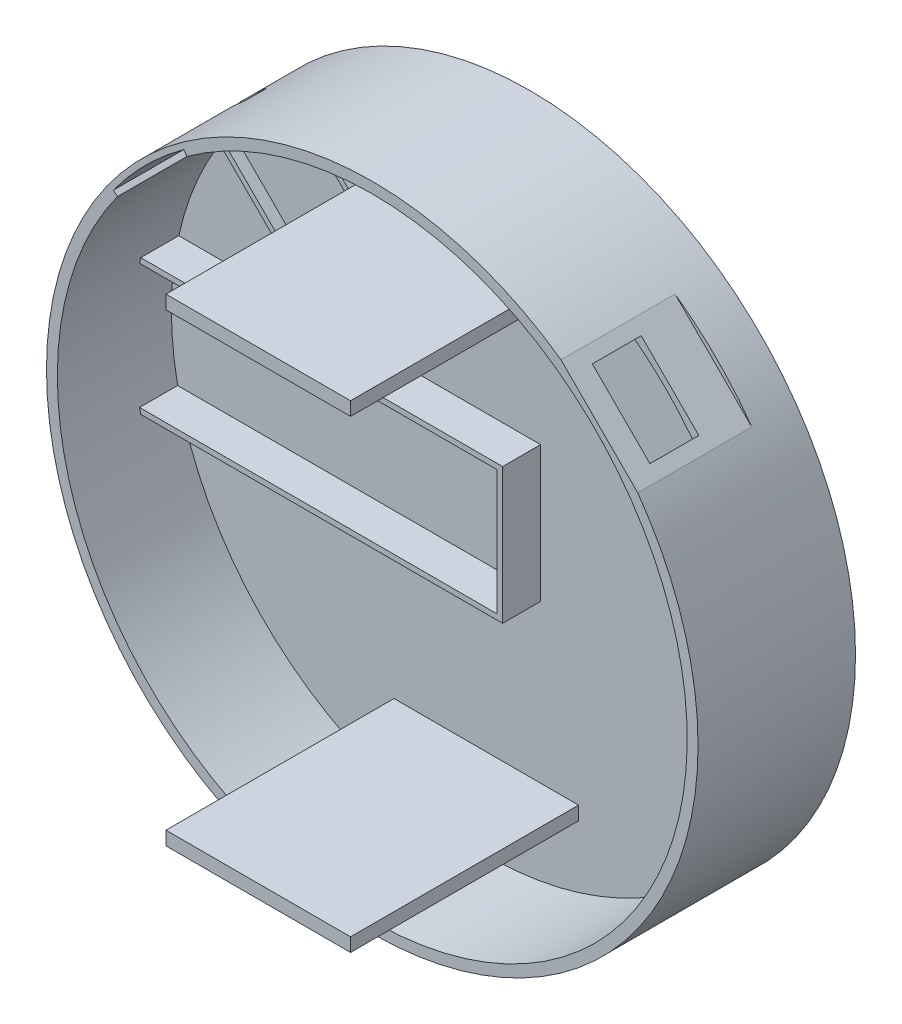
SolidWorks part; units mm, degrees
ref_plane "Alzado" through (0, 0, 0) normal (0, 0, 1) x (1, 0, 0)
ref_plane "Planta" through (0, 0, 0) normal (0, 1, 0) x (1, 0, 0)
ref_plane "Vista lateral" through (0, 0, 0) normal (1, 0, 0) x (0, 0, -1)
sketch "Croquis1" plane through (0, 0, 0) normal (0, 0, 1) x (1, 0, 0)
  circle A0 centre (0, 0) radius 60
  dimension "D1" = 120
extrude "Saliente-Extruir1" add sketch "Croquis1" along normal blind 8
sketch "Croquis2" plane through (0, 0, 8) normal (0, 0, 1) x (1, 0, 0)
  line L0 (-56, 0) -> (-45, 0) construction
  line L1 (-56, 11.5) -> (9, 11.5)
  line L2 (-56, 11.5) -> (-56, -11.5) construction
  line L3 (-56, -11.5) -> (9, -11.5)
  line L4 (9, 11.5) -> (9, -11.5)
  line L5 (-57, 12.5) -> (-57, 11.5)
  line L6 (-57, -12.5) -> (10, -12.5)
  line L7 (10, 12.5) -> (10, -12.5)
  line L8 (-57, 12.5) -> (10, 12.5)
  line L9 (-56, -11.5) -> (-57, -11.5)
  line L10 (-56, 11.5) -> (-57, 11.5)
  line L11 (-57, -11.5) -> (-57, -12.5)
  line L13 (-57, 12.5) -> (-57, -12.5) construction
  point P4 (-56, 0)
  dimension "D1" = 23
  dimension "D2" = 65
  dimension "D3" = 11
  dimension "D4" = 45
  dimension "D5" = 1
extrude "Saliente-Extruir2" add sketch "Croquis2" along normal blind 7
sketch "Croquis3" plane through (0, 0, 8) normal (0, 0, 1) x (1, 0, 0)
  circle A0 centre (0, 0) radius 58
  circle A1 centre (0, 0) radius 60
  circle A2 centre (0, 0) radius 60
  dimension "D1" = 0
  dimension "D2" = 2
extrude "Saliente-Extruir3" add sketch "Croquis3" along normal blind 21
sketch "Croquis4" plane through (0, 0, 8) normal (0, 0, 1) x (1, 0, 0)
  line L0 (0, 0) -> (10, 0) construction
  line L1 (-17, 44) -> (17, 44)
  line L2 (-17, 44) -> (-17, 41.5)
  line L3 (-17, 41.5) -> (17, 41.5)
  line L4 (17, 44) -> (17, 41.5)
  line L5 (10, -12.5) -> (10, 12.5) construction
  line L6 (-17, -44) -> (-17, -41.5)
  line L7 (17, -44) -> (17, -41.5)
  line L8 (-17, -44) -> (17, -44)
  line L9 (-17, -41.5) -> (17, -41.5)
  point P4 (0, 41.5)
  dimension "D1" = 34
  dimension "D2" = 2.5
  dimension "D3" = 41.5
sketch "Croquis5" plane through (0, 0, 8) normal (0, 0, 1) x (1, 0, 0)
  line L0 (0, 0) -> (-50.8895, 50.8895) construction
  line L1 (0, 0) -> (10, 0) construction
  line L2 (-19.9848, 32.7551) -> (-34.1269, 46.8973)
  line L3 (-32.7551, 19.9848) -> (-46.8973, 34.1269)
  line L4 (-6.3852, -6.3852) -> (-57.2746, 44.5043) construction
  line L5 (-32.7551, 19.9848) -> (-19.9848, 32.7551) construction
  line L6 (6.3852, 6.3852) -> (-44.5043, 57.2746) construction
  line L7 (-33.4622, 19.2777) -> (-48.2043, 34.0198)
  line L8 (-19.2777, 33.4622) -> (-34.0198, 48.2043)
  line L9 (-33.4622, 19.2777) -> (-32.7551, 19.9848)
  line L10 (-19.9848, 32.7551) -> (-19.2777, 33.4622)
  arc A0 (-56.637, -12.5) -> (-56.637, 12.5) centre (0, 0) ccw construction
  arc A1 (-34.1269, 46.8973) -> (-46.8973, 34.1269) centre (0, 0) ccw
  arc A2 (-34.0198, 48.2043) -> (-48.2043, 34.0198) centre (0, 0) ccw
  dimension "D1" = 135
  dimension "D2" = 9.03
  dimension "D4" = 20
  dimension "D5" = 1
  dimension "D3" = 9.03
extrude "Saliente-Extruir4" add sketch "Croquis5" along normal blind 2
sketch "Croquis6" plane through (0, 0, 8) normal (0, 0, 1) x (1, 0, 0)
  line L0 (-47.7058, 34.7153) -> (-46.8973, 34.1269)
  line L1 (-34.7153, 47.7058) -> (-34.1269, 46.8973)
  arc A0 (-34.1269, 46.8973) -> (-46.8973, 34.1269) centre (0, 0) ccw construction
  arc A1 (-34.1269, 46.8973) -> (-46.8973, 34.1269) centre (0, 0) ccw
  arc A2 (-34.7153, 47.7058) -> (-47.7058, 34.7153) centre (0, 0) ccw
  dimension "D1" = 1
extrude "Cortar-Extruir1" cut sketch "Croquis6" along normal through all
sketch "Croquis7" plane through (0, 0, 8) normal (0, 0, 1) x (1, 0, 0)
  line L0 (0, 0) -> (-45.9619, 45.9619) construction
  line L1 (0, 0) -> (10, 0) construction
  line L2 (-35.3553, 42.4264) -> (-42.4264, 49.4975)
  line L3 (-42.4264, 35.3553) -> (-49.4975, 42.4264)
  line L4 (-3.5355, -3.5355) -> (-49.4975, 42.4264) construction
  line L5 (3.5355, 3.5355) -> (-42.4264, 49.4975) construction
  line L6 (-42.4264, 35.3553) -> (-35.3553, 42.4264)
  line L7 (-49.4975, 42.4264) -> (-42.4264, 49.4975)
  dimension "D1" = 135
  dimension "D4" = 10
  dimension "D5" = 10
  dimension "D6" = 65
  dimension "D2" = 5
  dimension "D3" = 5
extrude "Cortar-Extruir2" cut sketch "Croquis7" along normal blind 4 from offset 1.5
sketch "Croquis8" plane through (0, 0, 8) normal (0, 0, 1) x (1, 0, 0)
  line L0 (0, 0) -> (41.833, 41.833) construction
  line L1 (0, 0) -> (10, 0) construction
  line L4 (48.9041, 34.7619) -> (34.7619, 48.9041)
  circle A0 centre (0, 0) radius 60 construction
  arc A1 (48.9041, 34.7619) -> (34.7619, 48.9041) centre (0, 0) ccw
  point P5 (0, 0)
  point P7 (41.833, 41.833)
  dimension "D1" = 45
  dimension "D2" = 20
extrude "Cortar-Extruir3" cut sketch "Croquis8" along normal through all
sketch "Croquis9" plane through (41.833, 41.833, 0) normal (0.7071, 0.7071, 0) x (0, 0, -1)
  line L0 (-29, 10) -> (-29, -10) construction
  line L1 (-25, 7.5) -> (-16, 7.5)
  line L2 (-25, 7.5) -> (-25, -7.5)
  line L3 (-25, -7.5) -> (-16, -7.5)
  line L4 (-16, 7.5) -> (-16, -7.5)
  point P4 (-16, 0)
  point P7 (-29, 0)
  point P8 (-25, 0)
  dimension "D1" = 15
  dimension "D2" = 9
  dimension "D3" = 4
extrude "Cortar-Extruir4" cut sketch "Croquis9" against normal blind 4
extrude "Saliente-Extruir5" add sketch "Croquis4" along normal blind 42
